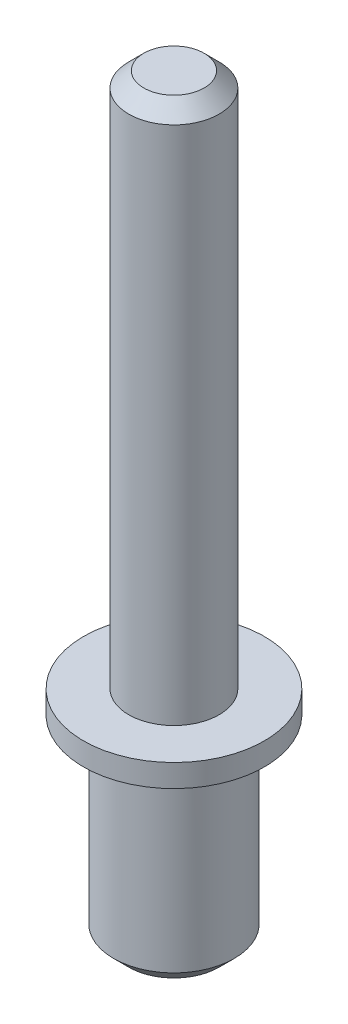
SolidWorks part; units mm, degrees
ref_plane "前视基准面" through (0, 0, 0) normal (0, 0, 1) x (1, 0, 0)
ref_plane "上视基准面" through (0, 0, 0) normal (0, 1, 0) x (1, 0, 0)
ref_plane "右视基准面" through (0, 0, 0) normal (1, 0, 0) x (0, 0, -1)
sketch "草图1" plane through (0, 0, 0) normal (0, 0, 1) x (1, 0, 0)
  line L0 (0, 0) -> (-4, 0)
  line L1 (-4, 0) -> (-4, 13)
  line L2 (-4, 13) -> (-6, 13)
  line L3 (-6, 13) -> (-6, 14.5)
  line L4 (-6, 14.5) -> (-3, 14.5)
  line L5 (-3, 14.5) -> (-3, 50)
  line L6 (-3, 50) -> (0, 50)
  line L7 (0, 50) -> (0, 0)
  dimension "D1" = 3
  dimension "D2" = 4
  dimension "D3" = 6
  dimension "D4" = 13
  dimension "D5" = 1.5
  dimension "D6" = 50
revolve "旋转1" add sketch "草图1" angle 360 about L7
cosmetic thread "装饰螺纹线1" parameters "D1"=10, "D2"=4.5
chamfer "倒角1" distance 1 angle 45 1 edges at (-4, 0, 0)
chamfer "倒角2" distance 1 angle 45 1 edges at (-3, 50, 0)
